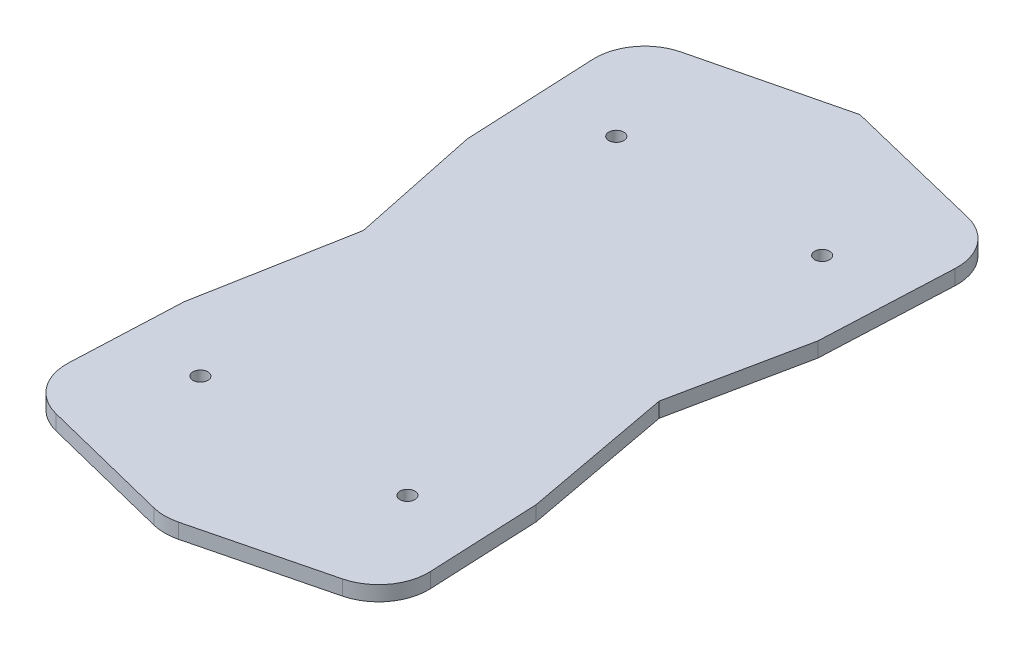
SolidWorks part; units mm, degrees
ref_plane "Alzado" through (0, 0, 0) normal (0, 0, 1) x (1, 0, 0)
ref_plane "Planta" through (0, 0, 0) normal (0, 1, 0) x (1, 0, 0)
ref_plane "Vista lateral" through (0, 0, 0) normal (1, 0, 0) x (0, 0, -1)
sketch "Croquis1" plane through (0, 0, 0) normal (0, 1, 0) x (1, 0, 0)
  line L2 (-35.3226, -4.5238) -> (-29.7138, 25.866)
  line L4 (0, 95.9232) -> (28.7456, 88.8733)
  line L5 (36.3535, 78.7092) -> (35.159, 52.308)
  line L6 (0, 95.9232) -> (-28.841, 88.8591)
  line L7 (35.159, 52.308) -> (29.6982, 25.9067)
  line L8 (-2.4254, -43.4705) -> (-28.7307, -36.8942)
  line L9 (-36.2958, -26.7554) -> (-35.3226, -4.5238)
  line L15 (2.4254, -43.4705) -> (28.8038, -36.8759)
  line L17 (36.368, -26.7182) -> (35.353, -4.4924)
  line L18 (-35.2218, 52.2736) -> (-29.7138, 25.866)
  line L20 (-36.4512, 78.6812) -> (-35.2218, 52.2736)
  line L21 (35.353, -4.4924) -> (29.6982, 25.9067)
  circle A0 centre (-20.6927, 67.6601) radius 1.5
  circle A1 centre (20.73, 67.6122) radius 1.5
  circle A2 centre (-20.7507, -15.8486) radius 1.5
  circle A3 centre (20.8099, -15.8064) radius 1.5
  arc A20 (28.7456, 88.8733) -> (36.3535, 78.7092) centre (26.3637, 79.1612) cw
  arc A21 (-28.841, 88.8591) -> (-36.4512, 78.6812) centre (-26.462, 79.1462) ccw
  arc A22 (28.8038, -36.8759) -> (36.368, -26.7182) centre (26.3784, -27.1745) ccw
  arc A23 (-28.7307, -36.8942) -> (-36.2958, -26.7554) centre (-26.3053, -27.1927) cw
  arc A24 (-2.4254, -43.4705) -> (2.4254, -43.4705) centre (0, -33.7691) ccw
  dimension "D1" = 10
  dimension "D2" = 10
  dimension "D3" = 10
extrude "Saliente-Extruir1" add sketch "Croquis1" along normal blind 3
